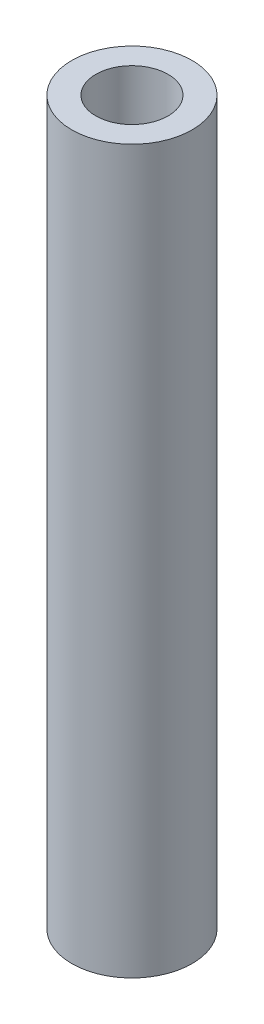
SolidWorks part; units mm, degrees
ref_plane "Ebene vorne" through (0, 0, 0) normal (0, 0, 1) x (1, 0, 0)
ref_plane "Ebene oben" through (0, 0, 0) normal (0, 1, 0) x (1, 0, 0)
ref_plane "Ebene rechts" through (0, 0, 0) normal (1, 0, 0) x (0, 0, -1)
sketch "Skizze1" plane through (0, 0, 0) normal (0, 1, 0) x (1, 0, 0)
  circle A0 centre (0, 0) radius 2.5
  circle A1 centre (0, 0) radius 1.5
  dimension "D1" = 1
  dimension "D2" = 5
extrude "Aufsatz-Linear austragen1" add sketch "Skizze1" along normal blind 30
